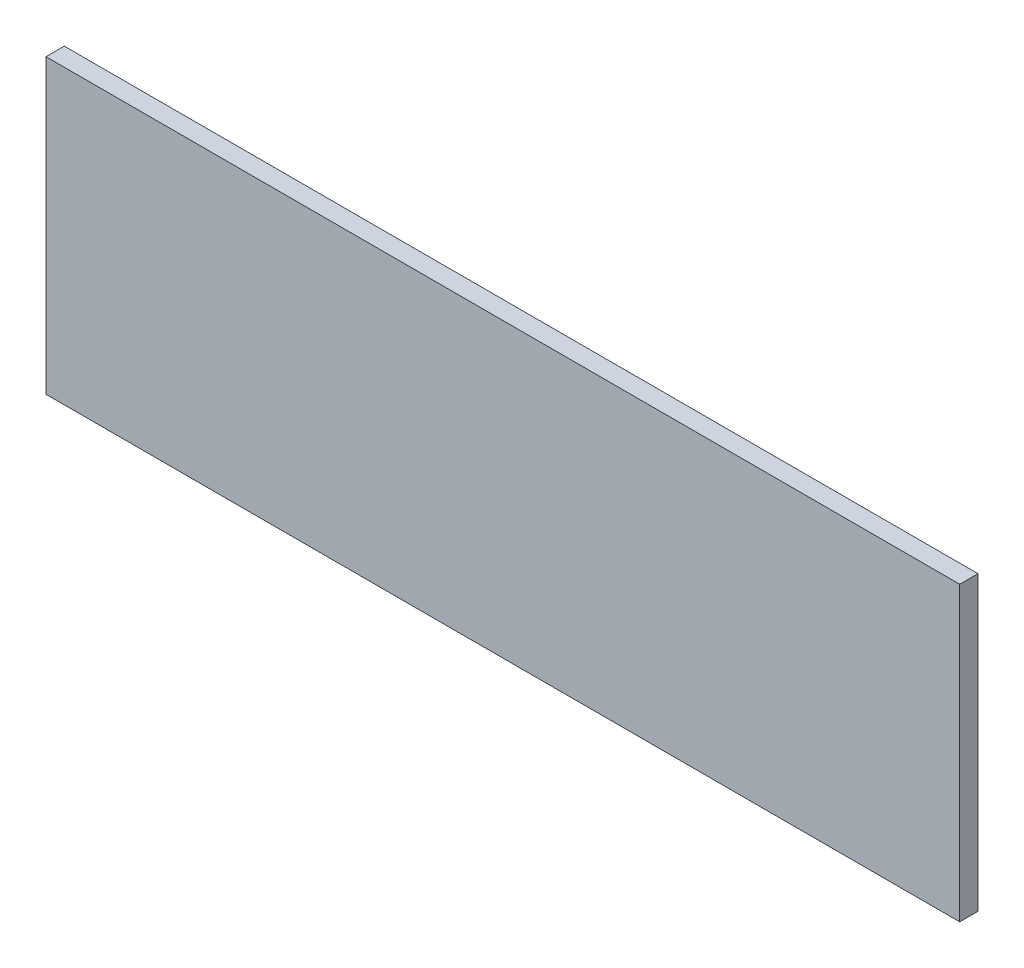
SolidWorks part; units mm, degrees
ref_plane "Front Plane" through (0, 0, 0) normal (0, 0, 1) x (1, 0, 0)
ref_plane "Top Plane" through (0, 0, 0) normal (0, 1, 0) x (1, 0, 0)
ref_plane "Right Plane" through (0, 0, 0) normal (1, 0, 0) x (0, 0, -1)
sketch "Sketch1" plane through (0, 0, 0) normal (0, 0, 1) x (1, 0, 0)
  line L0 (-365.6566, 215.9596) -> (634.3434, 215.9596)
  line L1 (634.3434, 215.9596) -> (634.3434, -104.0404)
  line L2 (634.3434, -104.0404) -> (-365.6566, -104.0404)
  line L3 (-365.6566, -104.0404) -> (-365.6566, 215.9596)
  dimension "D1" = 1000
  dimension "D2" = 320
extrude "Boss-Extrude1" add sketch "Sketch1" along normal blind 20
